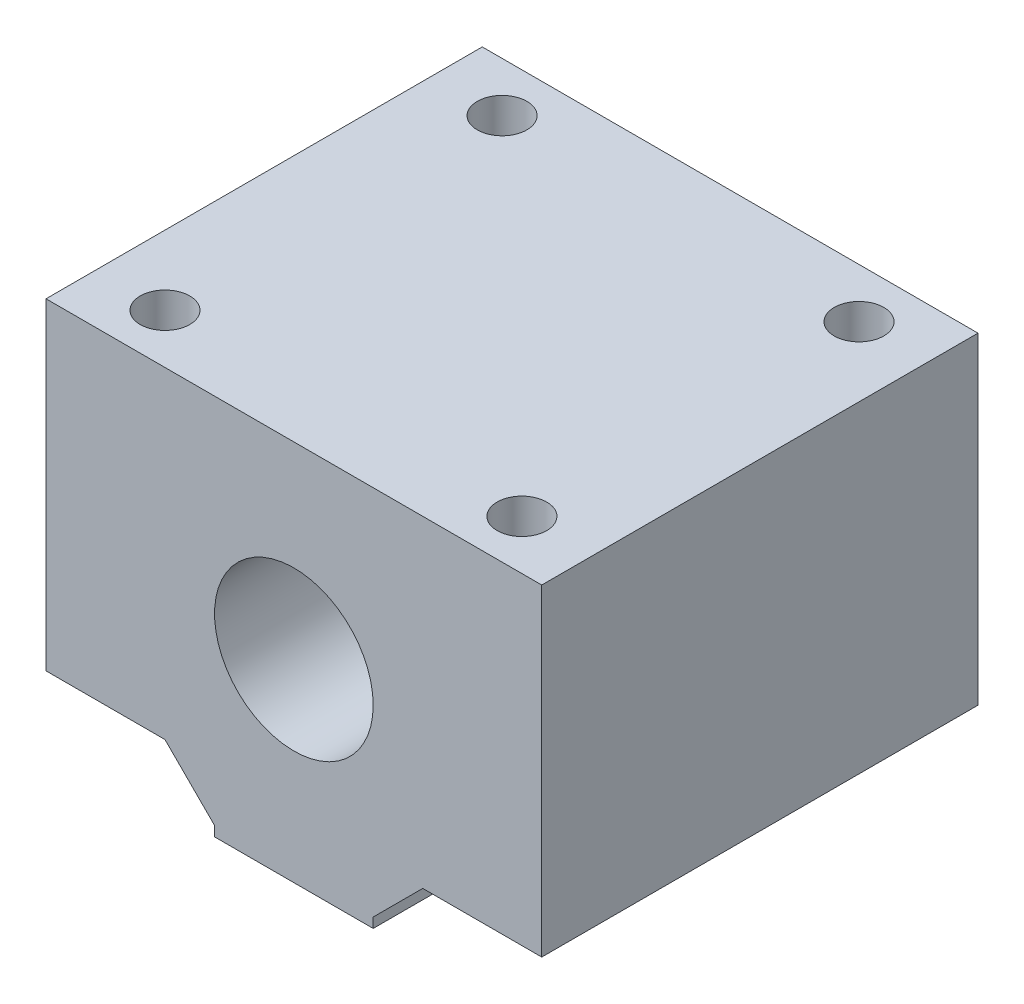
SolidWorks part; units mm, degrees
ref_plane "前视基准面" through (0, 0, 0) normal (0, 0, 1) x (1, 0, 0)
ref_plane "上视基准面" through (0, 0, 0) normal (0, 1, 0) x (1, 0, 0)
ref_plane "右视基准面" through (0, 0, 0) normal (1, 0, 0) x (0, 0, -1)
sketch "草图1" plane through (0, 0, 0) normal (0, 0, 1) x (1, 0, 0)
  line L0 (8, 0) -> (-8, 0)
  line L1 (-8, 0) -> (-8, 1)
  line L2 (-13, 6) -> (-25, 6)
  line L3 (-25, 6) -> (-25, 38.5)
  line L4 (-25, 38.5) -> (25, 38.5)
  line L5 (-8, 1) -> (-13, 6)
  line L6 (0, 0) -> (0, 38.5) construction
  line L7 (8, 1) -> (13, 6)
  line L8 (25, 6) -> (25, 38.5)
  line L9 (13, 6) -> (25, 6)
  line L10 (8, 0) -> (8, 1)
  circle A0 centre (0, 19.5) radius 8
  point P3 (-8, 6)
  point P16 (8, 6)
  dimension "D3" = 16
  dimension "D1" = 25
  dimension "D2" = 38.5
  dimension "D4" = 19
  dimension "D5" = 32.5
  dimension "D6" = 12
extrude "凸台-拉伸1" add sketch "草图1" along normal blind 44
sketch "草图2" plane through (0, 38.5, 0) normal (0, 1, 0) x (1, 0, 0)
  line L0 (0, 0) -> (0, -44) construction
  line L1 (25, -44) -> (-25, -44) construction
  line L2 (25, -22) -> (-25, -22) construction
  line L3 (25, -44) -> (25, 0) construction
  line L4 (-25, -44) -> (-25, 0) construction
  circle A0 centre (-18, -5) radius 2.5
  circle A1 centre (18, -5) radius 2.5
  circle A2 centre (18, -39) radius 2.5
  circle A3 centre (-18, -39) radius 2.5
  dimension "D1" = 5
  dimension "D4" = 34
  dimension "D2" = 5
  dimension "D3" = 7
extrude "切除-拉伸1" cut sketch "草图2" against normal through all
